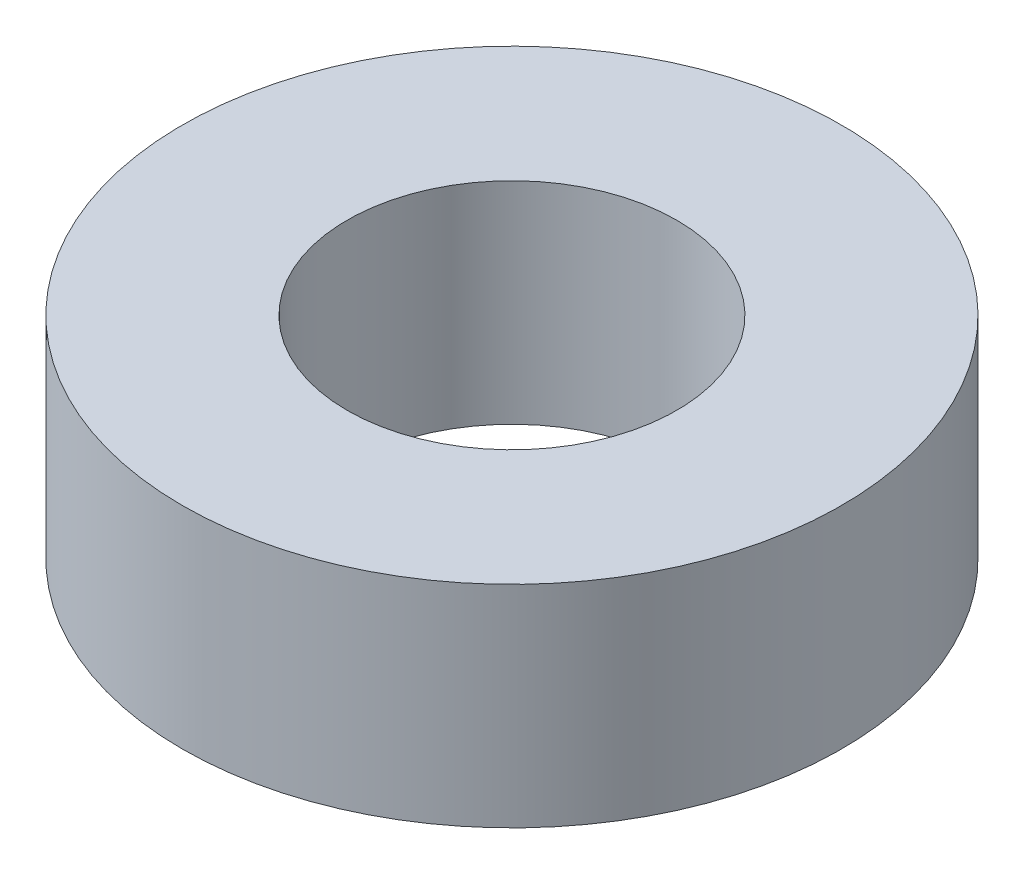
SolidWorks part; units mm, degrees
ref_plane "Front Plane" through (0, 0, 0) normal (0, 0, 1) x (1, 0, 0)
ref_plane "Top Plane" through (0, 0, 0) normal (0, 1, 0) x (1, 0, 0)
ref_plane "Right Plane" through (0, 0, 0) normal (1, 0, 0) x (0, 0, -1)
sketch "Sketch1" plane through (0, 0, 0) normal (0, 1, 0) x (1, 0, 0)
  circle A0 centre (0, 0) radius 12.5
  circle A1 centre (0, 0) radius 6.25
  dimension "D1" = 25
  dimension "D2" = 12.5
extrude "Boss-Extrude1" add sketch "Sketch1" along normal blind 8
